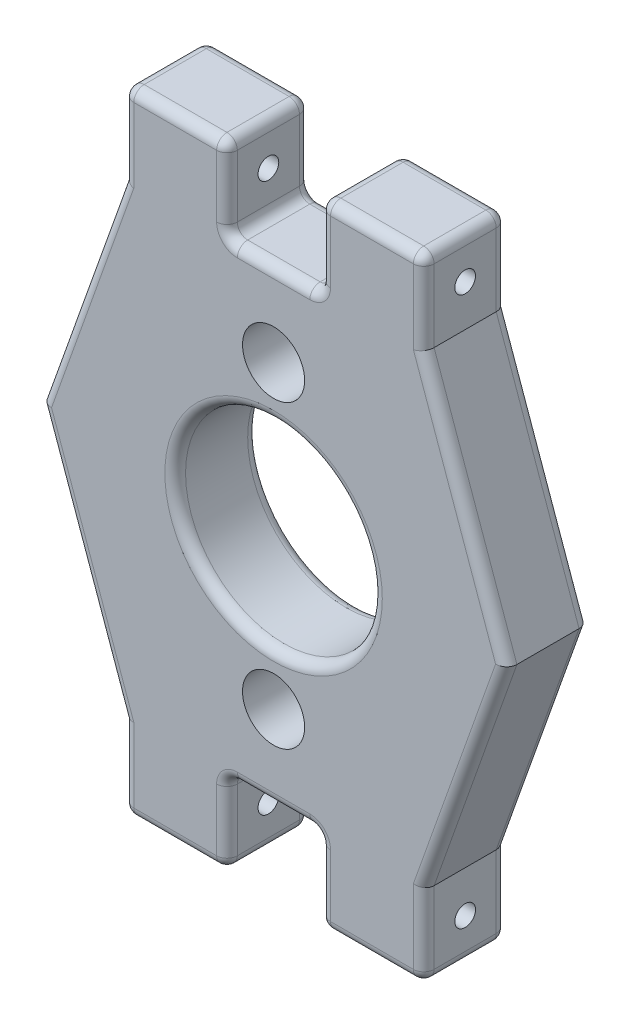
SolidWorks part; units mm, degrees
ref_plane "Front Plane" through (0, 0, 0) normal (0, 0, 1) x (1, 0, 0)
ref_plane "Top Plane" through (0, 0, 0) normal (0, 1, 0) x (1, 0, 0)
ref_plane "Right Plane" through (0, 0, 0) normal (1, 0, 0) x (0, 0, -1)
sketch "Sketch2" plane through (0, 0, 0) normal (0, 0, 1) x (1, 0, 0)
  line L0 (-22.5, 0) -> (22.5, 0) construction
  line L5 (22.5, 0) -> (14.5, 22.5)
  line L6 (-14.5, 22.5) -> (14.5, 22.5)
  line L7 (0, 22.5) -> (0, -22.5) construction
  line L8 (-22.5, 0) -> (-14.5, 22.5)
  line L9 (-22.5, 0) -> (-14.5, -22.5)
  line L10 (-14.5, -22.5) -> (14.5, -22.5)
  line L11 (22.5, 0) -> (14.5, -22.5)
  line L12 (-14.5, 22.5) -> (-14.5, 30.5)
  line L13 (-14.5, 30.5) -> (-4.5, 30.5)
  line L14 (-4.5, 30.5) -> (-4.5, 22.5)
  line L15 (4.5, 30.5) -> (4.5, 22.5)
  line L16 (14.5, 30.5) -> (4.5, 30.5)
  line L17 (14.5, 22.5) -> (14.5, 30.5)
  line L18 (-4.5, -30.5) -> (-4.5, -22.5)
  line L19 (14.5, -22.5) -> (14.5, -30.5)
  line L20 (-14.5, -22.5) -> (-14.5, -30.5)
  line L21 (4.5, -30.5) -> (4.5, -22.5)
  line L22 (14.5, -30.5) -> (4.5, -30.5)
  line L23 (-14.5, -30.5) -> (-4.5, -30.5)
  circle A0 centre (0, 0) radius 9.5
  point P0 (0, 0)
  dimension "D3" = 19
  dimension "D1" = 8
  dimension "D2" = 10
  dimension "D4" = 45
  dimension "D5" = 14.5
extrude "Boss-Extrude1" add sketch "Sketch2" along normal blind 8 contours L11 L5 L6 L8 L9 L10 A0 | L14 L13 L12 L6 | L6 L17 L16 L15 | L22 L19 L10 L21 | L20 L23 L18 L10
fillet "Fillet1" radius 1 50 edges at (4.5, 22.5, 4) (14.5, 30.5, 4) (4.5, 30.5, 4) (-4.5, 22.5, 4) (-4.5, 30.5, 4) (-14.5, 30.5, 4) (-14.5, -30.5, 4) (-4.5, -30.5, 4) (-4.5, -22.5, 4) (4.5, -22.5, 4) (4.5, -30.5, 4) (14.5, -30.5, 4) (14.5, -26.5, 8) (9.5, -30.5, 8) (4.5, -26.5, 8) (0, -22.5, 8) (-4.5, -26.5, 8) (-9.5, -30.5, 8) (-14.5, -26.5, 8) (-18.5, -11.25, 8) (-18.5, 11.25, 8) (-14.5, 26.5, 8) (-9.5, 30.5, 8) (-4.5, 26.5, 8) (0, 22.5, 8) (4.5, 26.5, 8) (9.5, 30.5, 8) (14.5, 26.5, 8) (18.5, 11.25, 8) (18.5, -11.25, 8) (9.5, 0, 8) (14.5, -26.5, 0) (9.5, -30.5, 0) (4.5, -26.5, 0) (0, -22.5, 0) (-4.5, -26.5, 0) (-9.5, -30.5, 0) (-14.5, -26.5, 0) (-18.5, -11.25, 0) (-18.5, 11.25, 0) (-14.5, 26.5, 0) (-9.5, 30.5, 0) (-4.5, 26.5, 0) (0, 22.5, 0) (4.5, 26.5, 0) (9.5, 30.5, 0) (14.5, 26.5, 0) (18.5, 11.25, 0) (18.5, -11.25, 0) (9.5, 0, 0)
sketch "Sketch3" plane through (4.5, 0, 0) normal (-1, 0, 0) x (0, 0, 1)
  circle A0 centre (4, 26.5) radius 1
  dimension "D1" = 2
extrude "Cut-Extrude1" cut sketch "Sketch3" against normal through all both and the other way through all
mirror "Mirror1" about plane through (0, 0, 0) normal (0, 1, 0) of "Cut-Extrude1"
sketch "Sketch4" plane through (0, 0, 8) normal (0, 0, 1) x (1, 0, 0)
  line L0 (0, 0) -> (42.0958, 0) construction
  circle A0 centre (0, 14.5) radius 3
  circle A2 centre (0, -14.5) radius 3
  dimension "D1" = 6
  dimension "D3" = 14.5
extrude "Cut-Extrude2" cut sketch "Sketch4" against normal through all both and the other way through all
